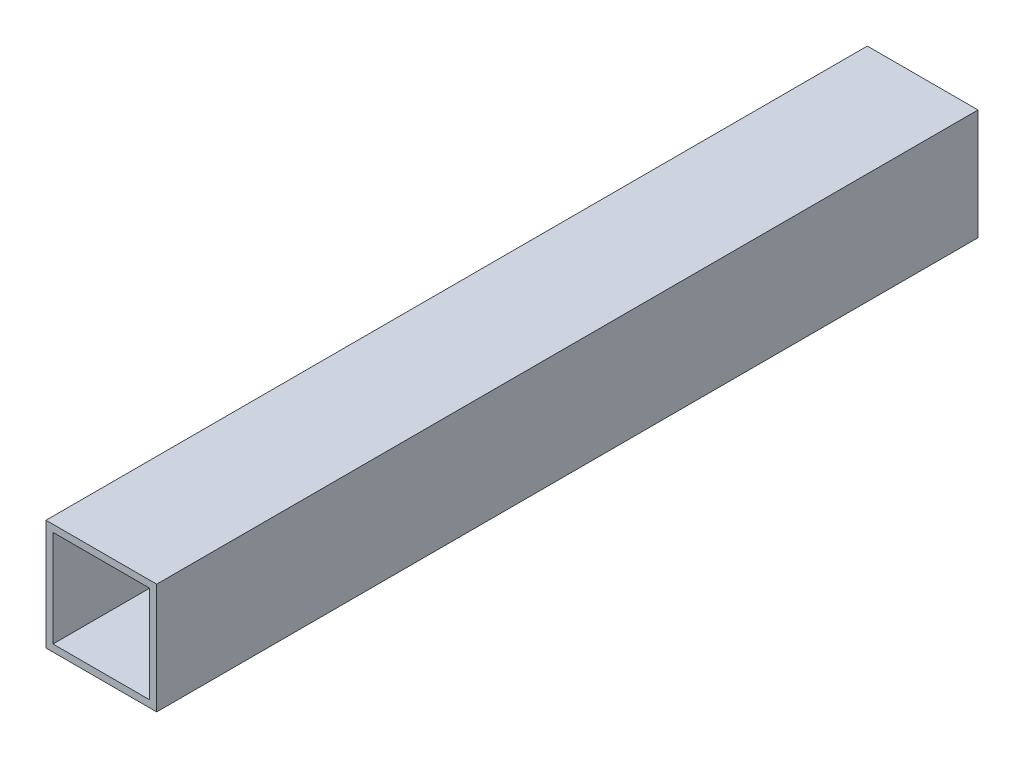
SolidWorks part; units mm, degrees
ref_plane "Front Plane" through (0, 0, 0) normal (0, 0, 1) x (1, 0, 0)
ref_plane "Top Plane" through (0, 0, 0) normal (0, 1, 0) x (1, 0, 0)
ref_plane "Right Plane" through (0, 0, 0) normal (1, 0, 0) x (0, 0, -1)
sketch "Sketch1" plane through (0, 0, 0) normal (0, 0, 1) x (1, 0, 0)
  line L0 (-8.3, 8.3) -> (-8.3, -8.3)
  line L1 (9.5, 9.5) -> (-9.5, 9.5)
  line L2 (9.5, 9.5) -> (9.5, -9.5)
  line L3 (9.5, -9.5) -> (-9.5, -9.5)
  line L4 (-9.5, 9.5) -> (-9.5, -9.5)
  line L5 (9.5, 9.5) -> (-9.5, -9.5) construction
  line L6 (9.5, -9.5) -> (-9.5, 9.5) construction
  line L7 (8.3, -8.3) -> (-8.3, -8.3)
  line L8 (8.3, 8.3) -> (8.3, -8.3)
  line L9 (8.3, 8.3) -> (-8.3, 8.3)
  point P0 (0, 0)
  dimension "D1" = 19
  dimension "D2" = 1.2
extrude "Boss-Extrude2" add sketch "Sketch1" along normal mid plane 141
